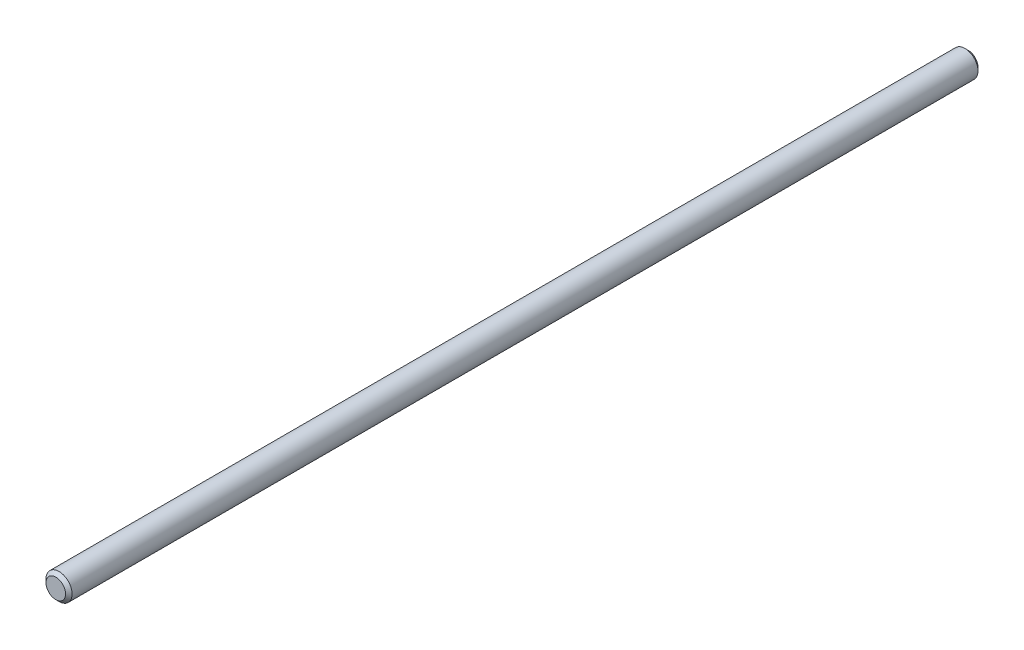
SolidWorks part; units mm, degrees
ref_plane "Front" through (0, 0, 0) normal (0, 0, 1) x (1, 0, 0)
ref_plane "Top" through (0, 0, 0) normal (0, 1, 0) x (1, 0, 0)
ref_plane "Right" through (0, 0, 0) normal (1, 0, 0) x (0, 0, -1)
sketch "Sketch1" plane through (0, 0, 0) normal (0, 0, 1) x (1, 0, 0)
  circle A0 centre (0, 0) radius 4
  dimension "D1" = 8
extrude "Boss-Extrude1" add sketch "Sketch1" along normal blind 280
chamfer "Chamfer1" distance 1 angle 45 2 edges at (4, 0, 280) (4, 0, 0)
